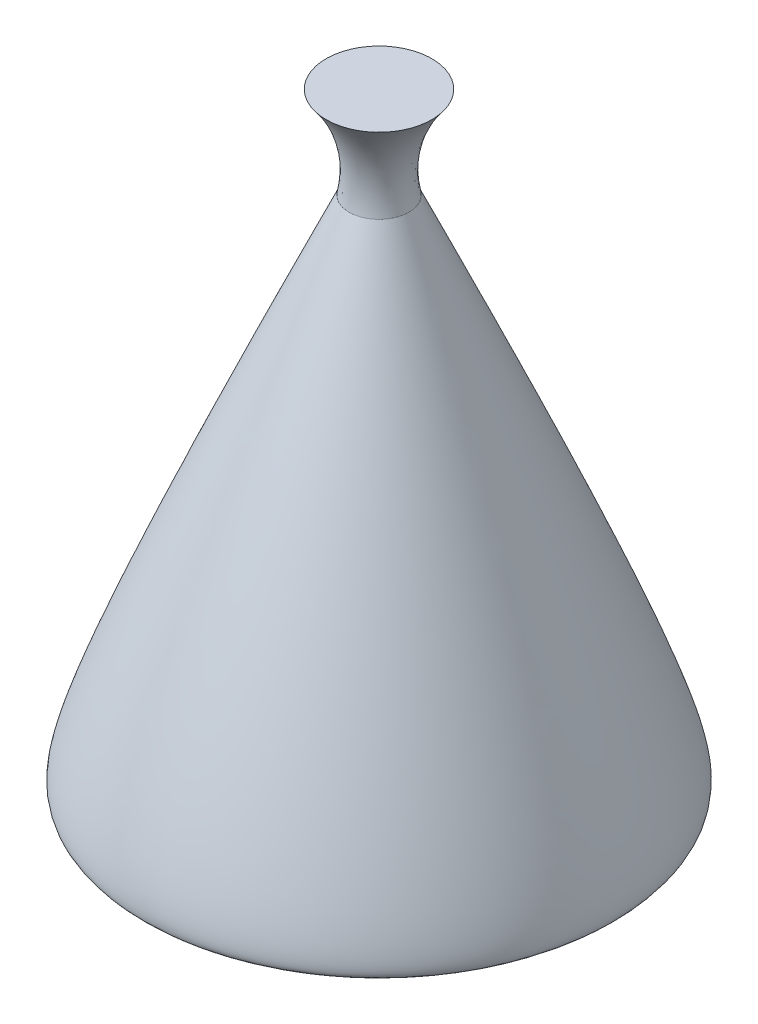
SolidWorks part; units mm, degrees
ref_plane "Front Plane" through (0, 0, 0) normal (0, 0, 1) x (1, 0, 0)
ref_plane "Top Plane" through (0, 0, 0) normal (0, 1, 0) x (1, 0, 0)
ref_plane "Right Plane" through (0, 0, 0) normal (1, 0, 0) x (0, 0, -1)
ref_axis "Axis1" through (0, 10.8396, 0) along (0, -1, 0)
sketch "Sketch3" plane through (0, 0, 0) normal (0, 0, 1) x (1, 0, 0)
  line L1 (0, -30.3505) -> (0, 30.3505) construction
  line L2 (-10.551, -21.7514) -> (0, -21.7514)
  line L3 (-2.4087, 5.84) -> (0, 5.84)
  line L5 (0, 5.84) -> (0, -21.7514)
  line L6 (-1.3615, 1.6618) -> (-11.9266, -21.7514) construction
  line L7 (-1.3615, 1.6618) -> (-11.9266, -21.7514) construction
  line L8 (-11.9266, -21.7514) -> (-10.551, -21.7514) construction
  spline S0 degree 2 poles (-1.3615, 1.6618) (-0.8996, 3.8911) (-2.4087, 5.84) knots 0 0 0 1 1 1
  spline S1 degree 2 poles (-1.3615, 1.6618) (-11.9266, -21.7514) (-10.551, -21.7514) knots 0 0 0 1 1 1
  point P20 (0, -21.7514)
revolve "Revolve9" add sketch "Sketch3" angle 360 about axis through (0, 10.8396, 0) along (0, -1, 0)
